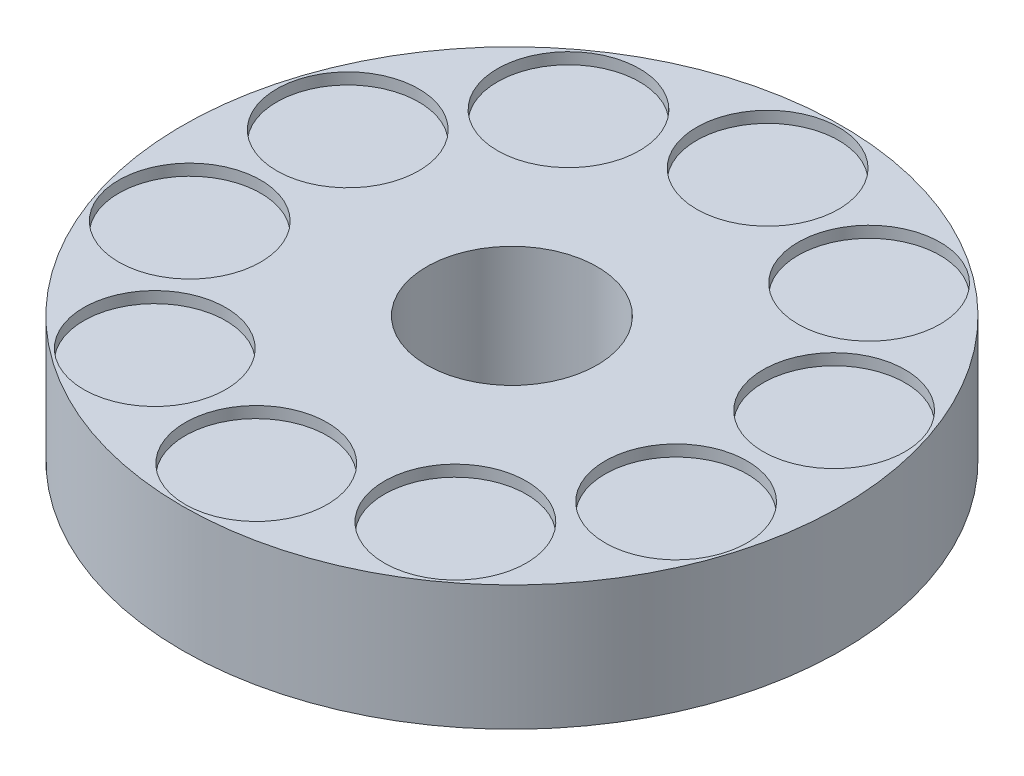
SolidWorks part; units mm, degrees
ref_plane "Front Plane" through (0, 0, 0) normal (0, 0, 1) x (1, 0, 0)
ref_plane "Top Plane" through (0, 0, 0) normal (0, 1, 0) x (1, 0, 0)
ref_plane "Right Plane" through (0, 0, 0) normal (1, 0, 0) x (0, 0, -1)
sketch "Sketch1" plane through (0, 0, 0) normal (1, 0, 0) x (0, 0, -1)
  line L0 (0, 42.6402) -> (0, -44.4546) construction
  line L1 (-45, 11) -> (-15, 11)
  line L2 (-15, 11) -> (-15, -11)
  line L3 (-15, -11) -> (-18, -11)
  line L4 (-18, -11) -> (-18, 7)
  line L5 (-18, 7) -> (-45, 7)
  line L9 (-45, 11) -> (-45, 7) construction
  line L10 (-45, 11) -> (-58, 11)
  line L11 (-58, 11) -> (-58, -11)
  line L12 (-58, -11) -> (-55, -11)
  line L13 (-55, -11) -> (-55, 7)
  line L14 (-55, 7) -> (-45, 7)
  point P5 (-15, 0)
  dimension "D1" = 30
  dimension "D2" = 4
  dimension "D4" = 13
  dimension "D5" = 3
  dimension "D6" = 45
  dimension "D7" = 3
  dimension "D8" = 18
revolve "Revolve1" add sketch "Sketch1" angle 360 about L0
sketch "Sketch2" plane through (0, 11, 0) normal (0, 1, 0) x (1, 0, 0)
  circle A0 centre (0, 0) radius 45 construction
  circle A1 centre (0, 45) radius 12.5
  circle A2 centre (26.4503, 36.4058) radius 12.5
  circle A3 centre (42.7975, 13.9058) radius 12.5
  circle A4 centre (42.7975, -13.9058) radius 12.5
  circle A5 centre (26.4503, -36.4058) radius 12.5
  circle A6 centre (0, -45) radius 12.5
  circle A7 centre (-26.4503, -36.4058) radius 12.5
  circle A8 centre (-42.7975, -13.9058) radius 12.5
  circle A9 centre (-42.7975, 13.9058) radius 12.5
  circle A10 centre (-26.4503, 36.4058) radius 12.5
  point P21 (0, 0)
  dimension "D1" = 25
  dimension "D3" = 90
  dimension "D2" = 10
extrude "Cut-Extrude1" cut sketch "Sketch2" against normal blind 2
sketch "Sketch3" plane through (0, 0, 0) normal (1, 0, 0) x (0, 0, -1)
  line L7 (-16.6207, -11) -> (-16.6207, 9)
  line L8 (-58, -11) -> (58, -11) construction
  line L9 (-16.6207, 9) -> (-31.6207, 9)
  line L10 (-31.6207, 9) -> (-16.6207, -11)
  line L11 (-15, -11) -> (15, -11) construction
  line L12 (-15, -11) -> (15, -11) construction
  dimension "D1" = 15
  dimension "D2" = 20
extrude "Boss-Extrude1" add sketch "Sketch3" along normal mid plane 3
pattern_circular "CirPattern1" count 6 over 360 about axis through (0, 0, 0) along (0, 1, 0) of "Boss-Extrude1"
